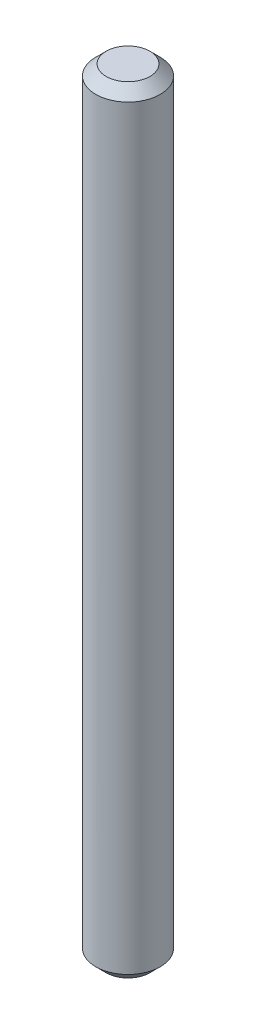
SolidWorks part; units mm, degrees
ref_plane "Front Plane" through (0, 0, 0) normal (0, 0, 1) x (1, 0, 0)
ref_plane "Top Plane" through (0, 0, 0) normal (0, 1, 0) x (1, 0, 0)
ref_plane "Right Plane" through (0, 0, 0) normal (1, 0, 0) x (0, 0, -1)
sketch "Sketch1" plane through (0, 0, 0) normal (0, 1, 0) x (1, 0, 0)
  circle A0 centre (0, 0) radius 1.5824
  dimension "D1" = 3.1648
extrude "Boss-Extrude1" add sketch "Sketch1" along normal mid plane 38.1
chamfer "Chamfer1" distance 0.508 angle 45
